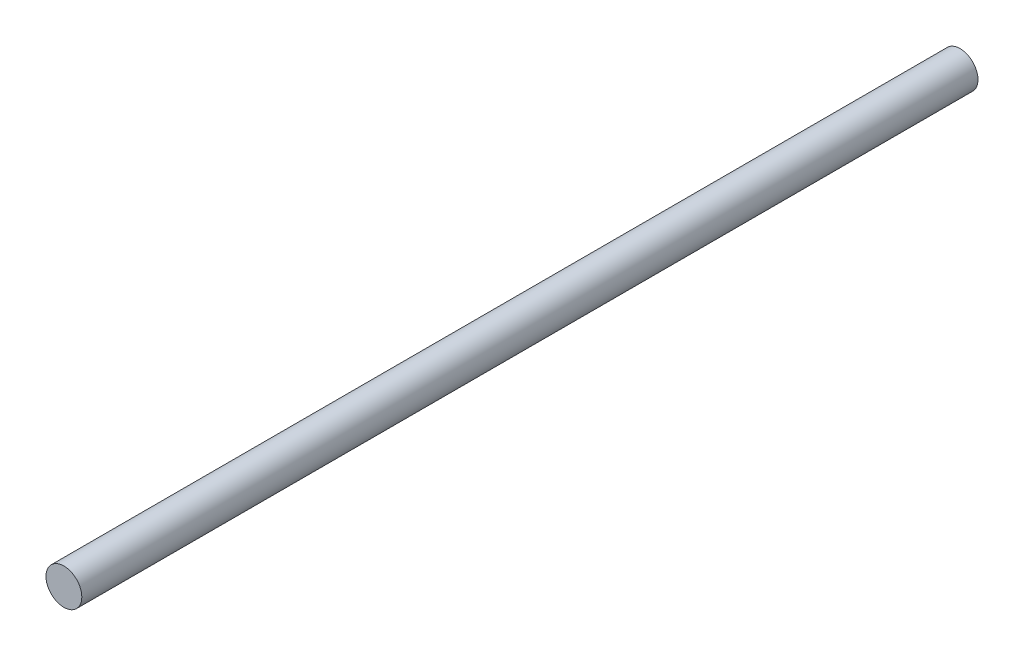
SolidWorks part; units mm, degrees
material "AISI 304"
ref_plane "Front Plane" through (0, 0, 0) normal (0, 0, 1) x (1, 0, 0)
ref_plane "Top Plane" through (0, 0, 0) normal (0, 1, 0) x (1, 0, 0)
ref_plane "Right Plane" through (0, 0, 0) normal (1, 0, 0) x (0, 0, -1)
sketch "Sketch2" plane through (0, 0, 0) normal (0, 0, 1) x (1, 0, 0)
  circle A0 centre (0, 0) radius 1.5
  dimension "D1" = 3
extrude "Boss-Extrude1" add sketch "Sketch2" along normal blind 75
